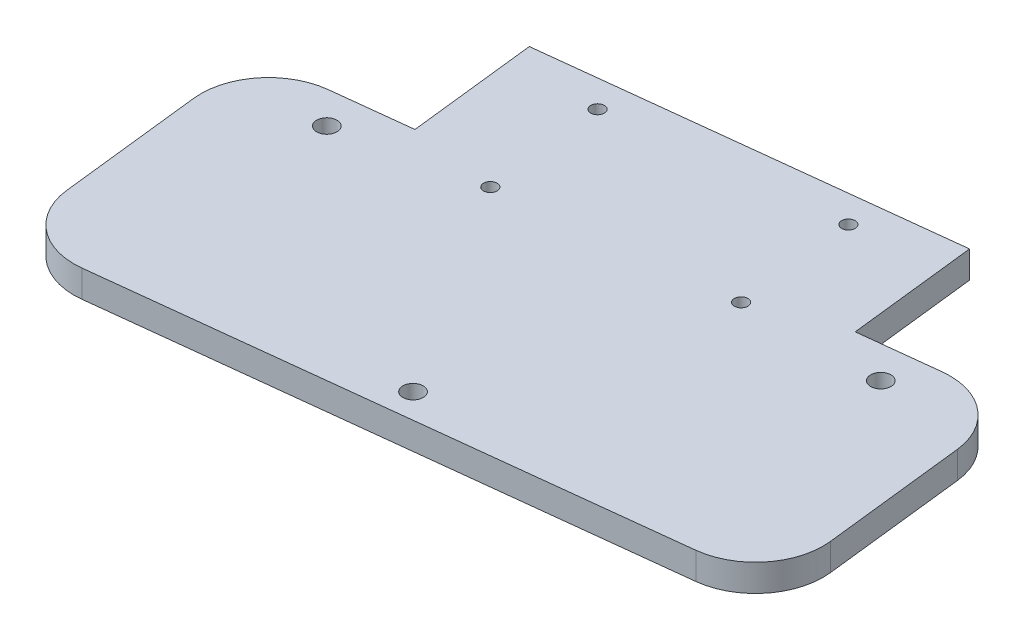
SolidWorks part; units mm, degrees
ref_plane "Front Plane" through (0, 0, 0) normal (0, 0, 1) x (1, 0, 0)
ref_plane "Top Plane" through (0, 0, 0) normal (0, 1, 0) x (1, 0, 0)
ref_plane "Right Plane" through (0, 0, 0) normal (1, 0, 0) x (0, 0, -1)
sketch "Sketch1" plane through (0, 0, 0) normal (0, 1, 0) x (1, 0, 0)
  line L0 (4.9161, -180.9962) -> (11.7351, -241.0893) construction
  line L1 (-43.5958, -205.8072) -> (-22.1351, -203.372)
  line L2 (-22.1351, -203.372) -> (-24.298, -184.3112)
  line L3 (-24.298, -184.3112) -> (34.1302, -177.6811)
  line L4 (34.1302, -177.6811) -> (36.2931, -196.7419)
  line L8 (36.2931, -196.7419) -> (57.7538, -194.3067)
  line L9 (57.7538, -194.3067) -> (62.4099, -235.339)
  line L10 (62.4099, -235.339) -> (-38.9397, -246.8395)
  line L11 (-38.9397, -246.8395) -> (-43.5958, -205.8072)
  line L12 (11.2789, -179.7828) -> (11.2789, 11.1383) construction
  line L13 (-11.2268, -187.294) -> (22.0596, -183.5169) construction
  circle A0 centre (-29.0931, -209.4452) radius 1.5
  circle A1 centre (44.435, -201.1017) radius 1.5
  circle A2 centre (11.2789, -237.0694) radius 1.5
  circle A3 centre (11.2789, -237.0694) radius 1.5 construction
  circle A4 centre (-9.1978, -205.1747) radius 1
  circle A5 centre (-11.2268, -187.294) radius 1
  circle A6 centre (22.0596, -183.5169) radius 1
  circle A10 centre (44.435, -201.1017) radius 1.5 construction
  circle A11 centre (24.0886, -201.3976) radius 1
  dimension "D6" = 3
  dimension "D1" = 102
extrude "Boss-Extrude1" add sketch "Sketch1" along normal blind 4
fillet "Fillet1" radius 10 1 edges at (-38.9397, 2, 246.8395)
fillet "Fillet2" radius 10 1 edges at (62.4099, 2, 235.339)
fillet "Fillet3" radius 10 1 edges at (57.7538, 2, 194.3067)
fillet "Fillet4" radius 10 1 edges at (-43.5958, 2, 205.8072)
